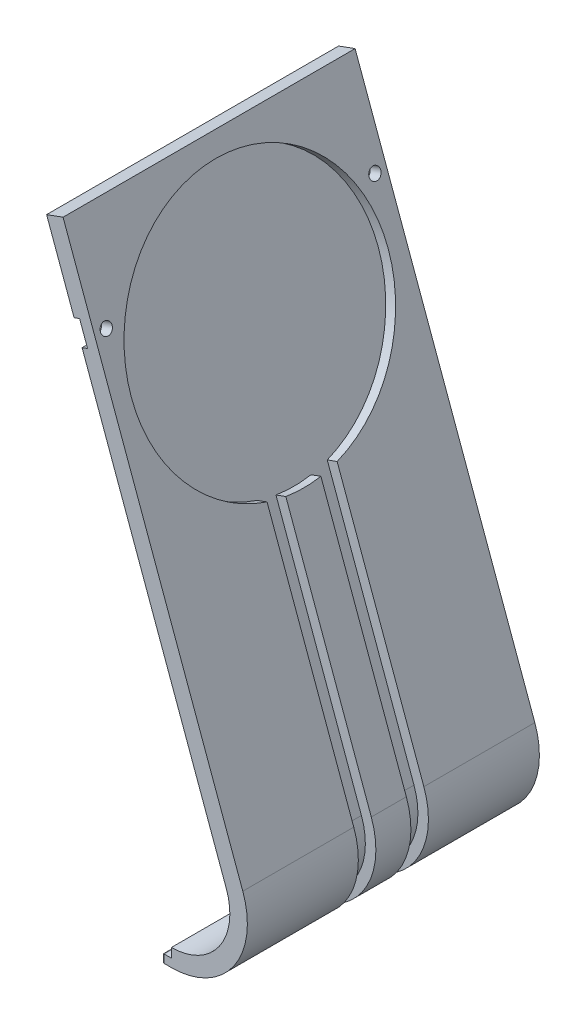
SolidWorks part; units mm, degrees
material "PLA"
ref_plane "前视基准面" through (0, 0, 0) normal (0, 0, 1) x (1, 0, 0)
ref_plane "上视基准面" through (0, 0, 0) normal (0, 1, 0) x (1, 0, 0)
ref_plane "右视基准面" through (0, 0, 0) normal (1, 0, 0) x (0, 0, -1)
other "Configuration Table"
sketch "草图2" plane through (0, 0, 0) normal (0, 0, 1) x (1, 0, 0)
  line L0 (38.2711, 18.4699) -> (5.8755, 107.4762) construction
  line L5 (38.2711, 18.4699) -> (7.4967, 103.022)
  line L10 (28.8742, 5.0497) -> (28.8742, 4.0497) construction
  line L11 (6.4731, 108.7579) -> (8.8224, 109.6129) construction
  arc A0 (28.8742, 5.0497) -> (38.2711, 18.4699) centre (28.8742, 15.0497) ccw
  arc A1 (28.8742, 5.0497) -> (38.2711, 18.4699) centre (28.8742, 15.0497) ccw construction
  dimension "D2" = 10
  dimension "D1" = 5.74
extrude "整体拉伸-薄壁1" add sketch "草图2" along normal mid plane 50 thin
sketch "草图4" plane through (42.5494, 15.4867, 0) normal (0.9397, 0.342, 0) x (0, 0, -1)
  line L0 (-25, 94.245) -> (25, 94.245) construction
  circle A0 centre (0, 68.845) radius 22
  dimension "D1" = 44
  dimension "D2" = 25.4
extrude "中间圆切除-拉伸1" cut sketch "草图4" against normal blind 1.8
sketch "草图3" plane through (0, 0, 0) normal (0, 0, 1) x (1, 0, 0)
  line L0 (41.0902, 19.4959) -> (10.3157, 104.0481) construction
  line L1 (41.0902, 19.4959) -> (10.3157, 104.0481) construction
  line L2 (28.8742, 2.0497) -> (28.8742, 5.0497) construction
  line L5 (39.3988, 18.8803) -> (24.836, 58.891)
  line L6 (39.3988, 18.8803) -> (8.6243, 103.4325) construction
  line L7 (28.8742, 3.8497) -> (28.8742, 3.8497) construction
  line L9 (24.836, 58.891) -> (26.5275, 59.5067) construction
  line L16 (24.836, 58.891) -> (23.81, 61.7101)
  line L17 (27.0769, 3.9492) -> (17.8463, 8.166) construction
  arc A0 (28.8742, 5.0497) -> (38.2711, 18.4699) centre (28.8742, 15.0497) ccw construction
  arc A1 (17.8463, 8.166) -> (41.0902, 19.4959) centre (28.8742, 15.0497) ccw construction
  arc A2 (28.8742, 3.8497) -> (39.3988, 18.8803) centre (28.8742, 15.0497) ccw
  dimension "D2" = 3
  dimension "D1" = 1.8
extrude "线槽切除-拉伸-薄壁1" cut sketch "草图3" against normal blind 3 from offset 6 thin
mirror "镜向1" about plane through (0, 0, 0) normal (0, 0, 1) of "线槽切除-拉伸-薄壁1"
sketch "草图11" plane through (28.8742, 0, 0) normal (-1, 0, 0) x (0, 0, 1)
  line L0 (-25, 2.0497) -> (-25, 5.0497) construction
  line L1 (-25, 3.4497) -> (-6.1, 3.4497)
  line L2 (-25, 3.4497) -> (-25, 2.0497)
  line L3 (-25, 2.0497) -> (-6.1, 2.0497)
  line L4 (-6.1, 3.4497) -> (-6.1, 2.0497)
  line L5 (25, 2.0497) -> (6, 2.0497) construction
  line L6 (6.1, 3.4497) -> (25, 3.4497)
  line L7 (6.1, 3.4497) -> (6.1, 2.0497)
  line L8 (6.1, 2.0497) -> (25, 2.0497)
  line L9 (25, 3.4497) -> (25, 2.0497)
  line L11 (-6, 2.0497) -> (-6, 3.8497) construction
  line L13 (6, 2.0497) -> (6, 3.8497) construction
  line L14 (25, 5.0497) -> (-25, 5.0497) construction
  dimension "D1" = 1.6
  dimension "D2" = 0.1
  dimension "D3" = 0.1
  dimension "D4" = 1.6
extrude "底部卡扣凸台-拉伸3" add sketch "草图11" along normal blind 1.5
fillet "底部卡扣圆角1" radius 0.25 8 edges at (27.3742, 3.4497, 15.55) (27.3742, 2.7497, 25) (27.3742, 2.0497, 15.55) (27.3742, 2.7497, 6.1) (27.3742, 3.4497, -15.55) (27.3742, 2.7497, -6.1) (27.3742, 2.0497, -15.55) (27.3742, 2.7497, -25)
sketch "草图12" plane through (39.7304, 14.4607, 0) normal (-0.9397, -0.342, 0) x (0, 0, 1)
  line L0 (-36.5, 80.4828) -> (36.5, 80.4828) construction
  line L2 (-25, 4.2665) -> (-25, 94.245) construction
  line L3 (25, 4.2665) -> (25, 94.245) construction
  circle A0 centre (23, 78.4828) radius 1
  circle A1 centre (-23, 78.4828) radius 1
  dimension "D1" = 2
  dimension "D2" = 2
  dimension "D3" = 2
  dimension "D4" = 2
  dimension "D5" = 2
  dimension "D6" = 2
extrude "螺丝孔" cut sketch "草图12" against normal through all
sketch "草图13" plane through (39.7304, 14.4607, 0) normal (-0.9397, -0.342, 0) x (0, 0, 1)
  line L0 (25, 4.2665) -> (25, 94.245) construction
  line L1 (23, 80.4828) -> (25, 80.4828)
  line L3 (23, 76.4828) -> (25, 76.4828)
  line L4 (25, 80.4828) -> (25, 76.4828)
  line L5 (-36.5, 80.4828) -> (36.5, 80.4828) construction
  line L6 (0, 94.245) -> (0, 78.3622) construction
  line L7 (25, 94.245) -> (-25, 94.245) construction
  line L8 (-25, 80.4828) -> (-25, 76.4828)
  line L9 (-23, 76.4828) -> (-25, 76.4828)
  line L10 (-23, 80.4828) -> (-25, 80.4828)
  arc A0 (23, 80.4828) -> (23, 76.4828) centre (23, 78.4828) ccw
  arc A1 (-23, 80.4828) -> (-23, 76.4828) centre (-23, 78.4828) cw
  dimension "D1" = 4
extrude "切除-拉伸1" cut sketch "草图13" against normal blind 1
